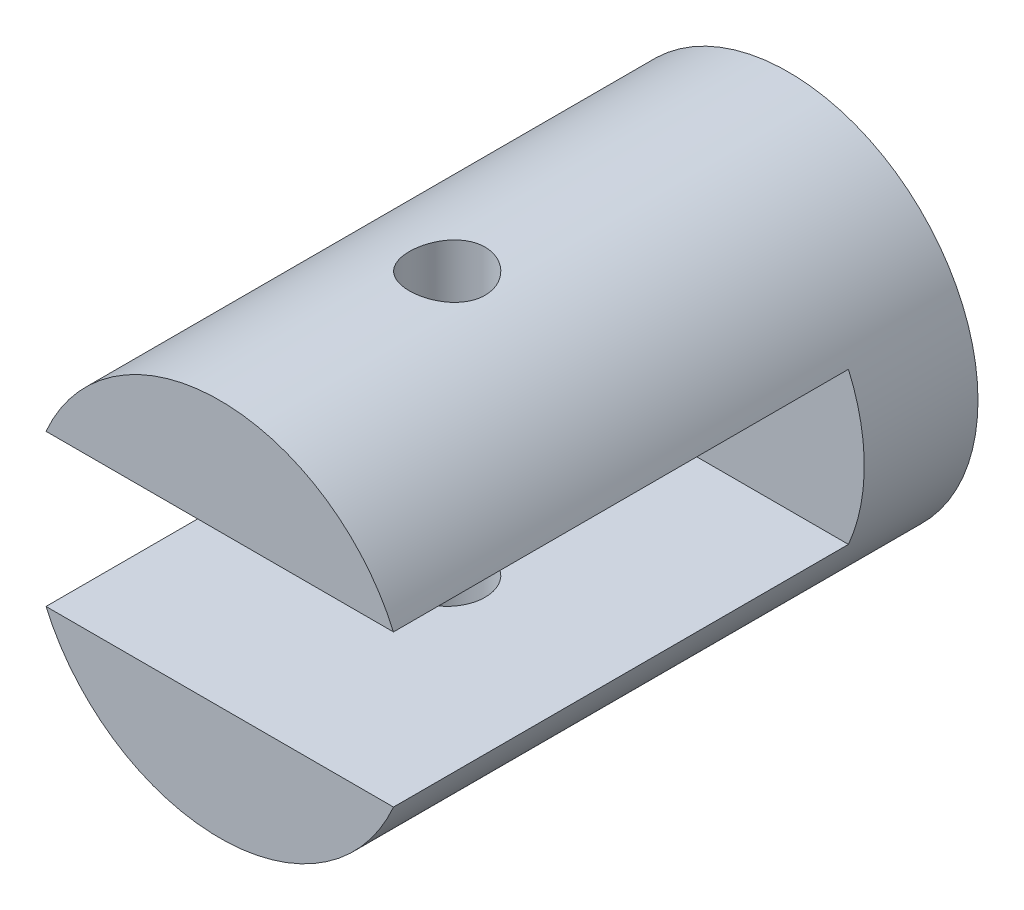
SolidWorks part; units mm, degrees
ref_plane "Front Plane" through (0, 0, 0) normal (0, 0, 1) x (1, 0, 0)
ref_plane "Top Plane" through (0, 0, 0) normal (0, 1, 0) x (1, 0, 0)
ref_plane "Right Plane" through (0, 0, 0) normal (1, 0, 0) x (0, 0, -1)
sketch "Sketch2" plane through (0, 0, 0) normal (0, 0, 1) x (1, 0, 0)
  circle A0 centre (0, 0) radius 50
  dimension "D1" = 100
extrude "Boss-Extrude1" add sketch "Sketch2" along normal blind 150
sketch "Sketch3" plane through (0, 0, 150) normal (0, 0, 1) x (1, 0, 0)
  line L0 (-45.8258, 20) -> (45.8258, 20)
  line L1 (45.8258, -20) -> (-45.8258, -20)
  line L2 (0, 0) -> (0, 20) construction
  line L3 (0, 0) -> (0, -20) construction
  arc A0 (-45.8258, 20) -> (-45.8258, -20) centre (0, 0) ccw construction
  circle A1 centre (0, 0) radius 50
  arc A2 (-45.8258, -20) -> (45.8258, -20) centre (0, 0) ccw
  arc A3 (45.8258, 20) -> (-45.8258, 20) centre (0, 0) ccw
  arc A4 (45.8258, -20) -> (45.8258, 20) centre (0, 0) ccw construction
  dimension "D2" = 40
  dimension "D1" = 0
extrude "Cut-Extrude1" cut sketch "Sketch3" against normal blind 120 flip side to cut
ref_plane "Plane2" through (0, 0, 90) normal (0, 0, 1) x (1, 0, 0)
sketch "Sketch5" plane through (0, 0, 90) normal (0, 0, 1) x (1, 0, 0)
  line L0 (0, 50) -> (0, -50)
  arc A0 (45.8258, 20) -> (-45.8258, 20) centre (0, 0) ccw construction
  arc A1 (-45.8258, -20) -> (45.8258, -20) centre (0, 0) ccw construction
sweep "Cut-Sweep1" cut path "Sketch5" circular profile diameter 20 parameters "D3"=20
